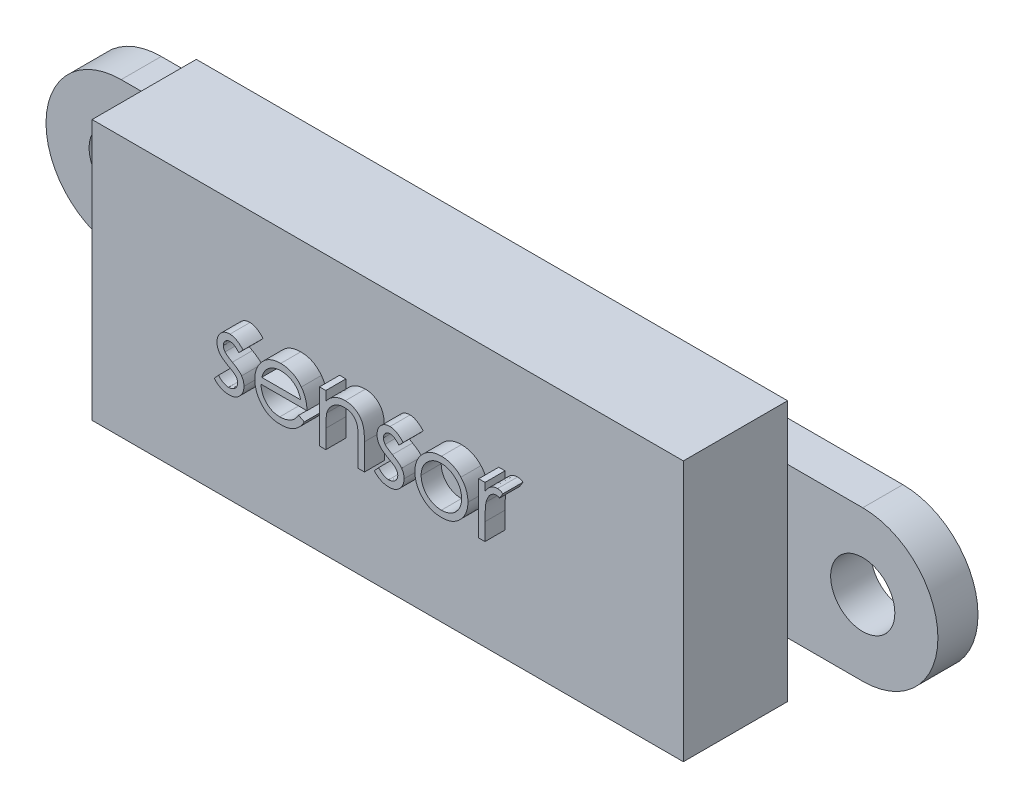
SolidWorks part; units mm, degrees
ref_plane "正面" through (0, 0, 0) normal (0, 0, 1) x (1, 0, 0)
ref_plane "平面" through (0, 0, 0) normal (0, 1, 0) x (1, 0, 0)
ref_plane "右側面" through (0, 0, 0) normal (1, 0, 0) x (0, 0, -1)
sketch "ｽｹｯﾁ1" plane through (0, 0, 0) normal (0, 0, 1) x (1, 0, 0)
  line L0 (-18.5, 0) -> (18.5, 0) construction
  line L1 (-18.5, 3.75) -> (18.5, 3.75)
  line L2 (-18.5, -3.75) -> (18.5, -3.75)
  arc A0 (-18.5, 3.75) -> (-18.5, -3.75) centre (-18.5, 0) ccw
  arc A1 (18.5, -3.75) -> (18.5, 3.75) centre (18.5, 0) ccw
  circle A2 centre (-18.5, 0) radius 1.6
  circle A3 centre (18.5, 0) radius 1.6
  point P3 (0, 0)
  dimension "D1" = 37
  dimension "D2" = 7.5
  dimension "D3" = 3.2
extrude "ﾎﾞｽ - 押し出し1" add sketch "ｽｹｯﾁ1" along normal blind 2
sketch "ｽｹｯﾁ2" plane through (0, 0, 2) normal (0, 0, 1) x (1, 0, 0)
  line L1 (-14.75, 6.5) -> (14.75, 6.5)
  line L2 (-14.75, 6.5) -> (-14.75, -6.5)
  line L3 (-14.75, -6.5) -> (14.75, -6.5)
  line L4 (14.75, 6.5) -> (14.75, -6.5)
  line L5 (-14.75, 6.5) -> (14.75, -6.5) construction
  line L6 (-14.75, -6.5) -> (14.75, 6.5) construction
  point P0 (0, 0)
  dimension "D1" = 29.5
  dimension "D2" = 13
extrude "ﾎﾞｽ - 押し出し2" add sketch "ｽｹｯﾁ2" along normal blind 5.2
sketch "ｽｹｯﾁ3" plane through (0, 0, 7.2) normal (0, 0, 1) x (1, 0, 0)
  text T0 "sensor"
extrude "ﾎﾞｽ - 押し出し3" add sketch "ｽｹｯﾁ3" along normal blind 1
